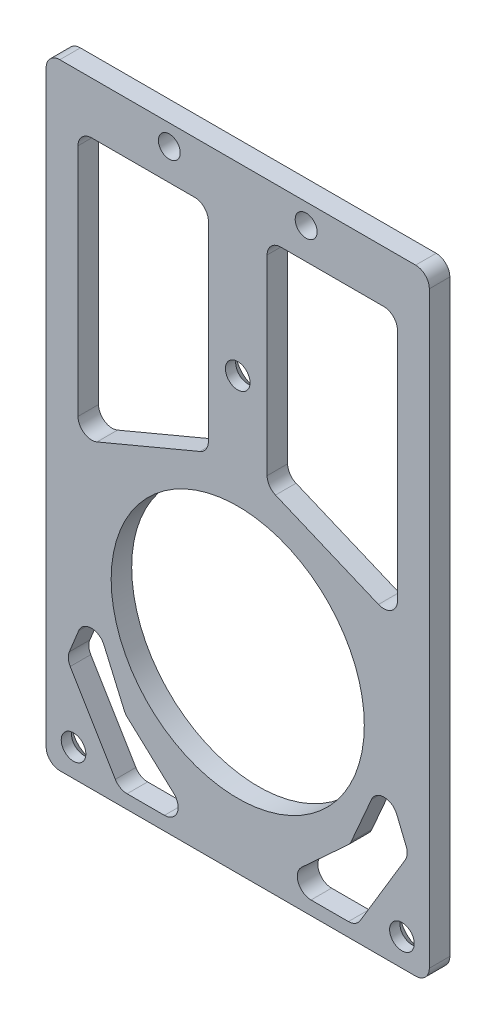
SolidWorks part; units mm, degrees
material "Hexcel AS4C (3000 丝)"
ref_plane "前视基准面" through (0, 0, 0) normal (0, 0, 1) x (1, 0, 0)
ref_plane "上视基准面" through (0, 0, 0) normal (0, 1, 0) x (1, 0, 0)
ref_plane "右视基准面" through (0, 0, 0) normal (1, 0, 0) x (0, 0, -1)
sketch "草图1" plane through (0, 0, 0) normal (0, 0, 1) x (1, 0, 0)
  line L0 (0, 0) -> (0, 45) construction
  line L1 (-28, 45) -> (28, 45)
  line L2 (-28, 45) -> (-28, -45)
  line L3 (-28, -45) -> (28, -45)
  line L4 (28, 45) -> (28, -45)
  line L5 (-28, 45) -> (28, -45) construction
  line L6 (-28, -45) -> (28, 45) construction
  circle A0 centre (10, 42) radius 1.6
  circle A2 centre (-10, 42) radius 1.6
  point P0 (0, 0)
  dimension "D2" = 3.2
  dimension "D3" = 20
  dimension "D4" = 3
  dimension "D1" = 56
  dimension "D5" = 90
extrude "凸台-拉伸1" add sketch "草图1" along normal blind 3
sketch "草图2" plane through (0, 0, 3) normal (0, 0, 1) x (1, 0, 0)
  line L0 (0, 45) -> (0, -45) construction
  line L1 (28, 45) -> (-28, 45) construction
  line L2 (-28, -45) -> (28, -45) construction
  line L3 (-28, 45) -> (-28, -45) construction
  circle A0 centre (0, -17) radius 18.5
  circle A5 centre (0, 18) radius 1.6
  circle A6 centre (24, -41) radius 1.6
  circle A7 centre (-24, -41) radius 1.6
  point P17 (0, -17)
  dimension "D1" = 62
  dimension "D2" = 37
  dimension "D3" = 3.2
  dimension "D4" = 4
  dimension "D6" = 35
  dimension "D5" = 4
extrude "切除-拉伸1" cut sketch "草图2" against normal through all
fillet "圆角1" radius 2 4 edges at (28, 45, 1.5) (-28, 45, 1.5) (28, -45, 1.5) (-28, -45, 1.5)
sketch "草图3" plane through (0, 0, 3) normal (0, 0, 1) x (1, 0, 0)
  line L0 (-23.345, 37.4321) -> (-4.2951, 37.4321)
  line L1 (-4.2951, 37.4321) -> (-4.2951, 6.1669)
  line L2 (-4.2951, 6.1669) -> (-23.345, -1.8311)
  line L3 (-23.345, -1.8311) -> (-23.345, 37.4321)
  line L4 (0, 0) -> (0, 58.9542) construction
  line L5 (4.2951, 6.1669) -> (23.345, -1.8311)
  line L6 (4.2951, 37.4321) -> (4.2951, 6.1669)
  line L7 (23.345, 37.4321) -> (4.2951, 37.4321)
  line L8 (23.345, -1.8311) -> (23.345, 37.4321)
  line L9 (-21.4492, -21.5102) -> (-24.9983, -30.1858)
  line L10 (-24.9983, -30.1858) -> (-17.3086, -43.002)
  line L11 (-17.3086, -43.002) -> (-5.5768, -43.002)
  line L12 (-5.5768, -43.002) -> (-16.4213, -33.0448)
  line L13 (-21.4492, -21.5102) -> (-16.4213, -33.0448)
  line L14 (21.4492, -21.5102) -> (24.9983, -30.1858)
  line L15 (24.9983, -30.1858) -> (17.3086, -43.002)
  line L16 (17.3086, -43.002) -> (5.5768, -43.002)
  line L17 (5.5768, -43.002) -> (16.4213, -33.0448)
  line L18 (21.4492, -21.5102) -> (16.4213, -33.0448)
extrude "切除-拉伸2" cut sketch "草图3" against normal through all
fillet "圆角2" radius 2 18 edges at (-4.2951, 37.4321, 1.5) (-4.2951, 6.1669, 1.5) (-23.345, -1.8311, 1.5) (-23.345, 37.4321, 1.5) (-24.9983, -30.1858, 1.5) (-21.4492, -21.5102, 1.5) (-5.5768, -43.002, 1.5) (-17.3086, -43.002, 1.5) (24.9983, -30.1858, 1.5) (17.3086, -43.002, 1.5) (5.5768, -43.002, 1.5) (16.4213, -33.0448, 1.5) (21.4492, -21.5102, 1.5) (23.345, 37.4321, 1.5) (23.345, -1.8311, 1.5) (4.2951, 6.1669, 1.5) (4.2951, 37.4321, 1.5) (-16.4213, -33.0448, 1.5)
hole_wizard "M3 十字槽半沉头木螺钉的锥形沉头孔1" positions "草图4" profile "草图5" countersink size "M3" standard "GB" end condition through all
sketch "草图4" plane through (0, 0, 0) normal (0, 0, 1) x (1, 0, 0)
  point P0 (0, 18)
  point P3 (-24, -41)
  point P6 (24, -41)
sketch "草图5" plane through (0, 18, 0) normal (1, 0, 0) x (0, 1, 0)
  line L0 (0, 0) -> (0, 3)
  line L1 (0, 3) -> (1.8, 3)
  line L2 (1.8, 3) -> (1.8, 1.5)
  line L3 (1.8, 1.5) -> (3.3, 0)
  line L5 (3.3, 0) -> (0, 0)
  line L6 (-1.8, 1.5) -> (-3.3, 0) construction
  line L11 (0, -6.35) -> (0, 107.95) construction
  dimension "通孔孔直径" = 3.6
  dimension "通孔孔深度" = 3
  dimension "近端锥形沉头孔直径" = 6.6
  dimension "近端锥形沉头孔角度" = 90
